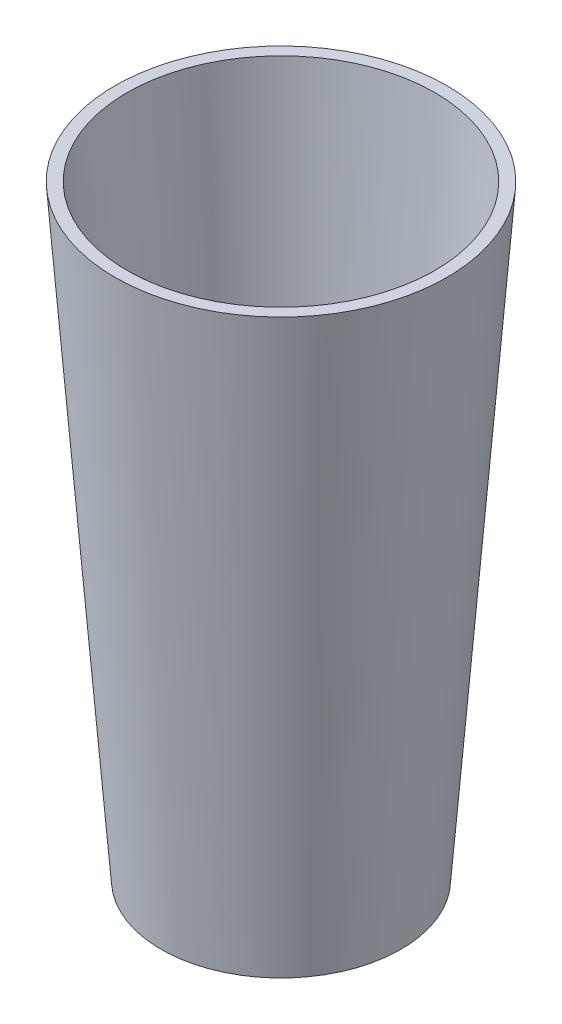
SolidWorks part; units mm, degrees
ref_plane "Front Plane" through (0, 0, 0) normal (0, 0, 1) x (1, 0, 0)
ref_plane "Top Plane" through (0, 0, 0) normal (0, 1, 0) x (1, 0, 0)
ref_plane "Right Plane" through (0, 0, 0) normal (1, 0, 0) x (0, 0, -1)
sketch "Sketch1" plane through (0, 0, 0) normal (0, 0, 1) x (1, 0, 0)
  line L0 (0, 0) -> (0, 151.333) construction
  line L1 (0, 151.333) -> (-41.529, 151.333) construction
  line L2 (-41.529, 151.333) -> (-30, 0)
  line L3 (-30, 0) -> (0, 0)
  line L4 (-38.5203, 151.333) -> (-27.296, 4)
  line L5 (-27.296, 4) -> (0, 4)
  line L6 (0, 0) -> (0, 4)
  line L7 (-41.529, 151.333) -> (-38.5203, 151.333)
  dimension "D1" = 151.333
  dimension "D2" = 41.529
  dimension "D3" = 30
  dimension "D4" = 3
  dimension "D5" = 4
revolve "Revolve1" add sketch "Sketch1" angle 360 about L0
